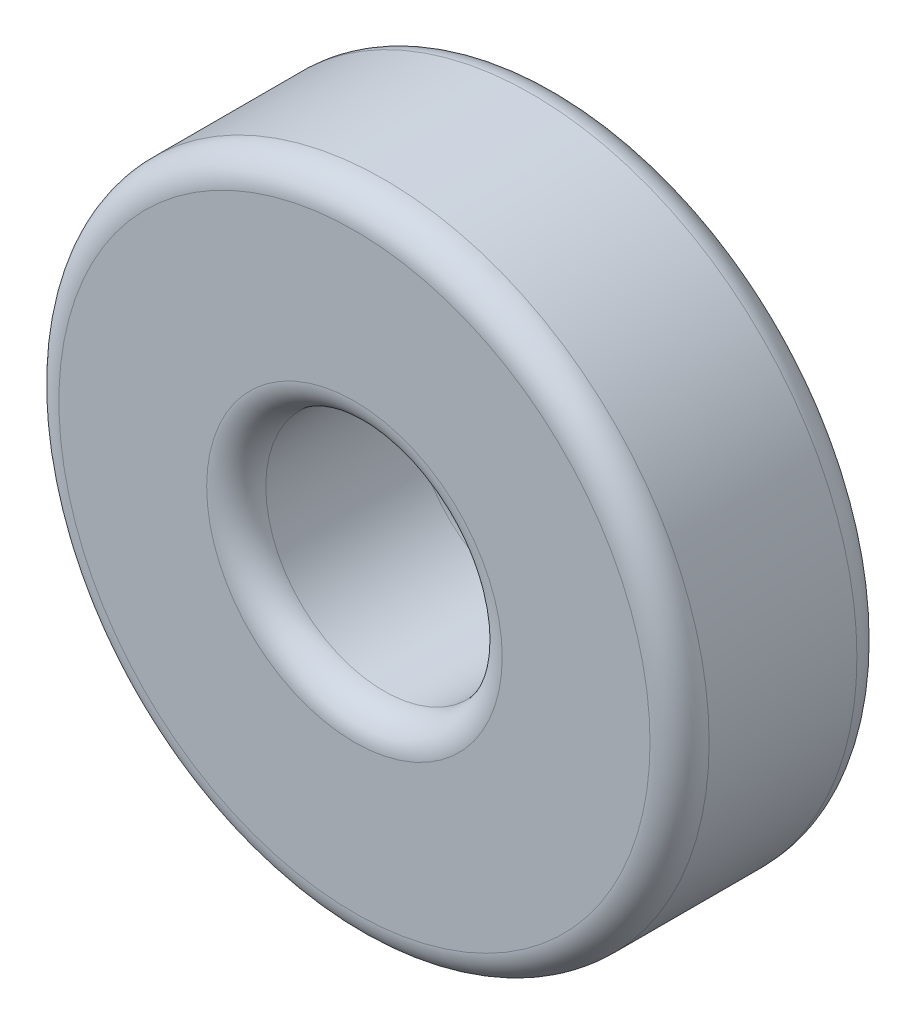
SolidWorks part; units mm, degrees
material "Cast Alloy Steel"
ref_plane "Front Plane" through (0, 0, 0) normal (0, 0, 1) x (1, 0, 0)
ref_plane "Top Plane" through (0, 0, 0) normal (0, 1, 0) x (1, 0, 0)
ref_plane "Right Plane" through (0, 0, 0) normal (1, 0, 0) x (0, 0, -1)
sketch "Sketch1" plane through (0, 0, 0) normal (0, 0, 1) x (1, 0, 0)
  circle A0 centre (0, 0) radius 4
  circle A1 centre (0, 0) radius 11
  dimension "D1" = 22
  dimension "D2" = 8
extrude "Boss-Extrude1" add sketch "Sketch1" along normal mid plane 7
fillet "Fillet4" radius 1 4 edges at (11, 0, -3.5) (11, 0, 3.5) (4, 0, -3.5) (4, 0, 3.5)
